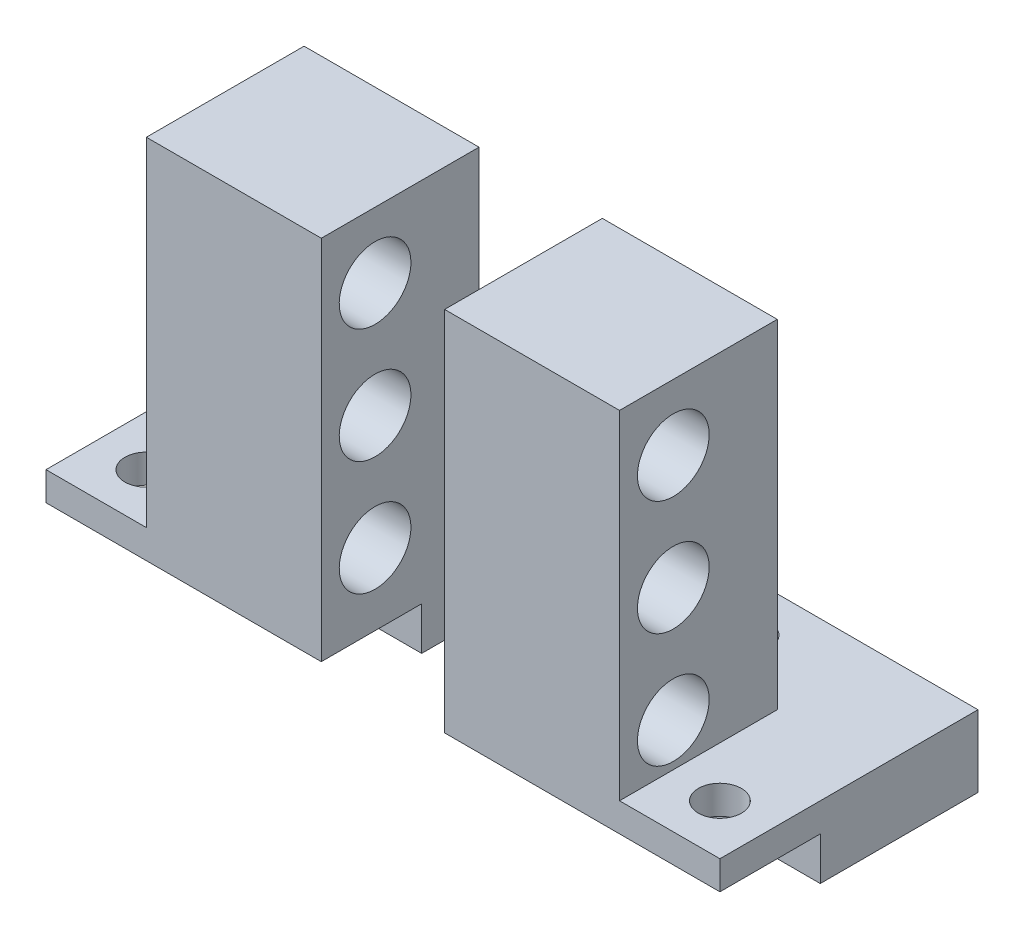
SolidWorks part; units mm, degrees
ref_plane "Front Plane" through (0, 0, 0) normal (0, 0, 1) x (1, 0, 0)
ref_plane "Top Plane" through (0, 0, 0) normal (0, 1, 0) x (1, 0, 0)
ref_plane "Right Plane" through (0, 0, 0) normal (1, 0, 0) x (0, 0, -1)
sketch "Sketch1" plane through (0, 0, 0) normal (0, 0, 1) x (1, 0, 0)
  line L0 (0, 0) -> (18, 0)
  line L1 (18, 0) -> (18, 28.578)
  line L2 (18, 28.578) -> (7, 28.578)
  line L3 (7, 28.578) -> (7, 5)
  line L4 (7, 5) -> (0, 5)
  line L5 (0, 5) -> (0, 0)
  dimension "D1" = 28.578
  dimension "D2" = 18
  dimension "D3" = 7
  dimension "D4" = 5
  dimension "D5" = 11
extrude "Boss-Extrude1" add sketch "Sketch1" along normal blind 11
sketch "Sketch3" plane through (0, 0, 0) normal (-1, 0, 0) x (0, 0, 1)
  line L1 (11, 0) -> (4, 0)
  line L2 (11, 0) -> (11, 3)
  line L3 (11, 3) -> (4, 3)
  line L4 (4, 0) -> (4, 3)
  dimension "D1" = 7
  dimension "D2" = 3
extrude "Cut-Extrude1" cut sketch "Sketch3" against normal up to body
sketch "Sketch4" plane through (7, 0, 0) normal (-1, 0, 0) x (0, 0, 1)
  line L0 (11, 5) -> (0, 5) construction
  line L1 (11, 28.578) -> (11, 5) construction
  circle A0 centre (7.25, 8) radius 2.5
  circle A1 centre (7.25, 16) radius 2.5
  circle A2 centre (7.25, 24) radius 2.5
  dimension "D1" = 5
  dimension "D2" = 8
  dimension "D3" = 8
  dimension "D4" = 3
  dimension "D5" = 3.75
extrude "Cut-Extrude2" cut sketch "Sketch4" against normal up to body
sketch "Sketch5" plane through (0, 5, 0) normal (0, 1, 0) x (1, 0, 0)
  line L0 (7, -11) -> (0, -11) construction
  line L1 (0, -11) -> (0, 0) construction
  circle A0 centre (3.5, -7.5) radius 1.5
  dimension "D1" = 3.5
  dimension "D2" = 3
  dimension "D3" = 3.5
extrude "Cut-Extrude3" cut sketch "Sketch5" against normal blind 11
ref_plane "Plane1" through (23.5, 0, 0) normal (1, 0, 0) x (0, 0, -1)
mirror "Mirror6" about plane through (23.5, 0, 0) normal (1, 0, 0) of bodies 104
sketch "Sketch6" plane through (0, 0, 0) normal (0, 0, -1) x (-1, 0, 0)
  line L1 (-47, 5) -> (0, 5)
  line L2 (-47, 5) -> (-47, 0)
  line L3 (-47, 0) -> (0, 0)
  line L4 (0, 5) -> (0, 0)
extrude "Boss-Extrude2" add sketch "Sketch6" along normal blind 7
sketch "Sketch7" plane through (0, 5, 0) normal (0, 1, 0) x (1, 0, 0)
  line L1 (0, 7) -> (47, 7) construction
  line L2 (23.5, 7) -> (23.5, -15.3699) construction
  circle A0 centre (12.5, 3.5) radius 1.5
  circle A1 centre (34.5, 3.5) radius 1.5
  dimension "D1" = 3
  dimension "D2" = 3.5
extrude "Cut-Extrude4" cut sketch "Sketch7" against normal up to surface (5 mm away) up to face at (23.5, 0, 0.25)
sketch "Sketch9" plane through (29, 0, 0) normal (-1, 0, 0) x (0, 0, 1)
  line L7 (11, 3) -> (11, 28.578)
  line L8 (11, 28.578) -> (0, 28.578)
  line L9 (0, 28.578) -> (0, 5)
  line L10 (0, 5) -> (0, 0)
  line L11 (0, 0) -> (4, 0)
  line L12 (4, 0) -> (4, 3)
  line L13 (4, 3) -> (11, 3)
  line L14 (11, 3) -> (11, 28.578)
  line L15 (11, 28.578) -> (0, 28.578)
  line L16 (0, 28.578) -> (0, 5)
  line L17 (0, 5) -> (0, 0)
  line L18 (0, 0) -> (4, 0)
  line L19 (4, 0) -> (4, 3)
  line L20 (4, 3) -> (11, 3)
  circle A0 centre (7.25, 24) radius 2.5 construction
  circle A1 centre (7.25, 16) radius 2.5 construction
  circle A2 centre (7.25, 8) radius 2.5 construction
  circle A3 centre (7.25, 24) radius 2.5
  circle A4 centre (7.25, 16) radius 2.5
  circle A5 centre (7.25, 8) radius 2.5
  dimension "D1" = 0
extrude "Boss-Extrude3" add sketch "Sketch9" along normal blind 1.2
sketch "Sketch10" plane through (18, 0, 0) normal (1, 0, 0) x (0, 0, -1)
  line L7 (-11, 28.578) -> (-11, 3)
  line L8 (-11, 3) -> (-4, 3)
  line L9 (-4, 3) -> (-4, 0)
  line L10 (-4, 0) -> (0, 0)
  line L11 (0, 0) -> (0, 5)
  line L12 (0, 5) -> (0, 28.578)
  line L13 (0, 28.578) -> (-11, 28.578)
  line L14 (-11, 28.578) -> (-11, 3)
  line L15 (-11, 3) -> (-4, 3)
  line L16 (-4, 3) -> (-4, 0)
  line L17 (-4, 0) -> (0, 0)
  line L18 (0, 0) -> (0, 5)
  line L19 (0, 5) -> (0, 28.578)
  line L20 (0, 28.578) -> (-11, 28.578)
  circle A0 centre (-7.25, 8) radius 2.5 construction
  circle A1 centre (-7.25, 16) radius 2.5 construction
  circle A2 centre (-7.25, 24) radius 2.5 construction
  circle A3 centre (-7.25, 8) radius 2.5
  circle A4 centre (-7.25, 16) radius 2.5
  circle A5 centre (-7.25, 24) radius 2.5
  dimension "D1" = 0
extrude "Boss-Extrude4" add sketch "Sketch10" along normal blind 1.2
